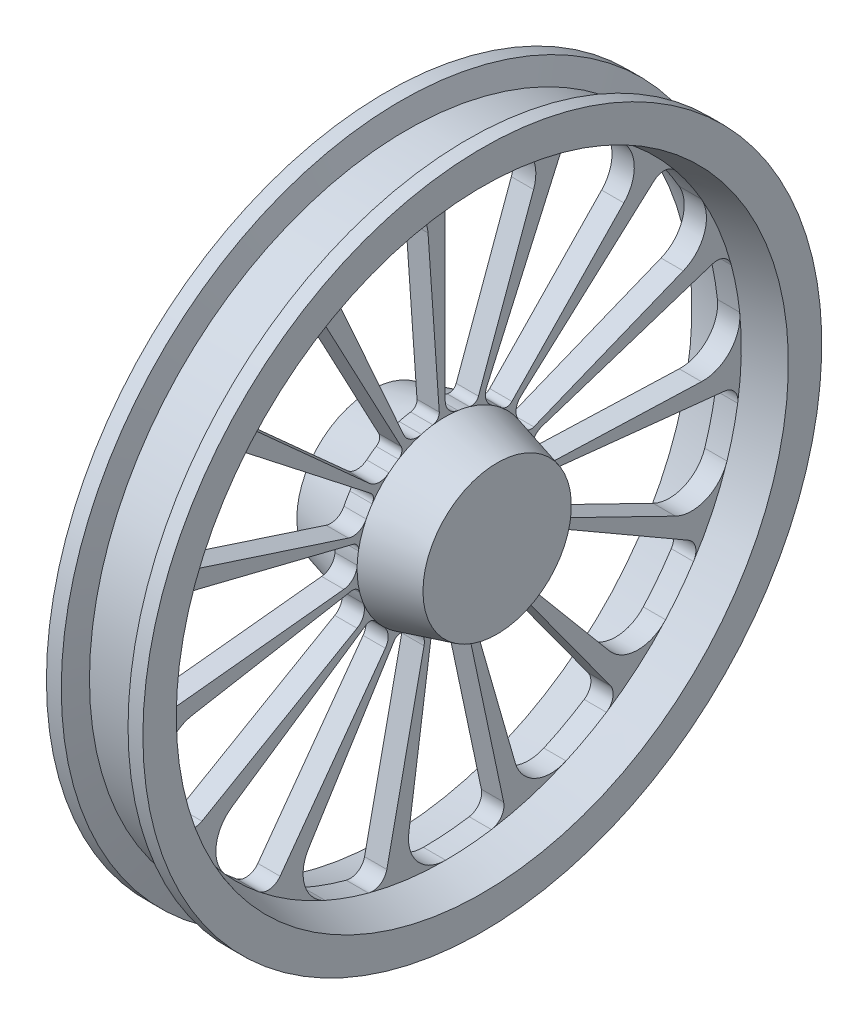
SolidWorks part; units mm, degrees
material "1060 Alloy"
ref_plane "Front Plane" through (0, 0, 0) normal (0, 0, 1) x (1, 0, 0)
ref_plane "Top Plane" through (0, 0, 0) normal (0, 1, 0) x (1, 0, 0)
ref_plane "Right Plane" through (0, 0, 0) normal (1, 0, 0) x (0, 0, -1)
sketch "Sketch1" plane through (0, 0, 0) normal (0, 1, 0) x (1, 0, 0)
  line L0 (0, 427.5) -> (0, -257.8979) construction
  line L1 (-372, 0) -> (372, 0) construction
  line L2 (-85, 0) -> (85, 0) construction
  line L3 (85, 0) -> (85, 100)
  line L4 (85, 100) -> (15, 118.7564)
  line L5 (15, 118.7564) -> (15, 399.1025)
  line L6 (15, 399.1025) -> (65, 412.5)
  line L7 (65, 412.5) -> (65, 457.5)
  line L8 (65, 457.5) -> (45, 457.5)
  line L9 (45, 457.5) -> (36.9615, 427.5)
  line L10 (36.9615, 427.5) -> (-36.9615, 427.5)
  line L11 (15, 118.7564) -> (91.7849, 118.7564) construction
  line L12 (-85, 0) -> (-85, 100)
  line L13 (36.9615, 427.5) -> (36.9615, 457.5) construction
  line L14 (15, 399.1025) -> (32.4139, 399.1025) construction
  line L15 (-85, 100) -> (-15, 118.7564)
  line L16 (-15, 118.7564) -> (-15, 399.1025)
  line L17 (-15, 399.1025) -> (-65, 412.5)
  line L18 (-65, 412.5) -> (-65, 457.5)
  line L19 (-65, 457.5) -> (-45, 457.5)
  line L20 (-45, 457.5) -> (-36.9615, 427.5)
  line L21 (-85, 0) -> (85, 0)
  point P4 (0, 0)
  point P8 (0, 0)
  point P21 (0, 0)
  dimension "D2" = 15
  dimension "D3" = 100
  dimension "D4" = 45
  dimension "D5" = 20
  dimension "D6" = 30
  dimension "D7" = 15
  dimension "D8" = 15
  dimension "D9" = 65
  dimension "D10" = 85
  dimension "D11" = 457.5
  dimension "D12" = 30
revolve "Revolve1" add sketch "Sketch1" angle 360 about L21
sketch "Sketch2" plane through (15, 0, 0) normal (1, 0, 0) x (0, 0, -1)
  line L0 (0, 457.5) -> (0, -457.5) construction
  line L1 (-457.5, 0) -> (457.5, 0) construction
  line L2 (0, 378.5746) -> (0, 137.3075)
  line L3 (119.0959, 324.4726) -> (44.8089, 120.3708)
  line L4 (153.9802, 345.8451) -> (55.848, 125.4366)
  line L5 (240.7744, 247.9799) -> (89.8942, 91.7388)
  line L6 (281.3358, 253.3159) -> (102.0394, 91.8767)
  line L7 (320.8208, 128.6091) -> (119.4359, 47.2443)
  line L8 (360.0459, 116.986) -> (130.5872, 42.4304)
  line L9 (345.3945, -12.9993) -> (128.3262, -5.4191)
  line L10 (376.5007, -39.5718) -> (136.5553, -14.3525)
  line L11 (310.2462, -152.3601) -> (115.0276, -57.1456)
  line L12 (327.8552, -189.2873) -> (118.9118, -68.6538)
  line L13 (221.4536, -265.3764) -> (81.8398, -98.991)
  line L14 (222.5206, -306.2733) -> (80.7073, -111.0841)
  line L15 (94.3697, -332.5067) -> (34.5011, -123.72)
  line L16 (78.7101, -370.3018) -> (28.5478, -134.307)
  line L17 (-49.0317, -342.1436) -> (-18.8032, -127.0567)
  line L18 (-78.7101, -370.3018) -> (-28.5478, -134.307)
  line L19 (-183.955, -292.6207) -> (-68.8562, -108.4241)
  line L20 (-222.5206, -306.2733) -> (-80.7073, -111.0841)
  line L21 (-287.0708, -192.5011) -> (-107.0033, -71.044)
  line L22 (-327.8552, -189.2873) -> (-118.9118, -68.6538)
  line L23 (-340.5495, -59.0963) -> (-126.6486, -21.3798)
  line L24 (-376.5007, -39.5718) -> (-136.5553, -14.3525)
  line L25 (-335.144, 84.5268) -> (-124.3952, 31.9812)
  line L26 (-360.0459, 116.986) -> (-130.5872, 42.4304)
  line L27 (-271.7892, 213.5344) -> (-100.6327, 79.8124)
  line L28 (-281.3358, 253.3159) -> (-102.0394, 91.8767)
  line L29 (-161.4395, 305.62) -> (-59.47, 113.8433)
  line L30 (-153.9802, 345.8451) -> (-55.848, 125.4366)
  line L31 (-23.1754, 344.8612) -> (-8.0243, 128.1896)
  circle A0 centre (0, 0) radius 457.5 construction
  arc A1 (0, 378.5746) -> (21.0551, 398.5468) centre (20, 378.5746) cw
  circle A2 centre (0, 0) radius 399.1025 construction
  arc A3 (0, 137.3075) -> (17.1173, 117.5164) centre (20, 137.3075) ccw
  circle A4 centre (0, 0) radius 118.7564 construction
  arc A5 (119.0959, 324.4726) -> (82.4393, 390.4953) centre (72.1112, 341.5736) ccw
  arc A6 (44.8089, 120.3708) -> (32.6616, 114.1767) centre (35.4119, 123.791) cw
  arc A8 (32.6616, 114.1767) -> (17.1173, 117.5164) centre (0, 0) ccw
  arc A10 (82.4393, 390.4953) -> (21.0551, 398.5468) centre (0, 0) ccw
  arc A11 (55.848, 125.4366) -> (63.4356, 100.3943) centre (74.1189, 117.3019) ccw
  arc A12 (76.2777, 91.0209) -> (63.4356, 100.3943) centre (0, 0) ccw
  arc A13 (89.8942, 91.7388) -> (76.2777, 91.0209) centre (82.7008, 98.6854) cw
  arc A14 (153.9802, 345.8451) -> (181.3384, 355.5267) centre (172.2511, 337.7104) cw
  arc A15 (234.1408, 323.2041) -> (181.3384, 355.5267) centre (0, 0) ccw
  arc A16 (240.7744, 247.9799) -> (234.1408, 323.2041) centre (204.8074, 282.7128) ccw
  arc A17 (102.0394, 91.8767) -> (98.7853, 65.9132) centre (115.422, 77.0138) ccw
  arc A18 (106.7047, 52.1268) -> (98.7853, 65.9132) centre (0, 0) ccw
  arc A19 (119.4359, 47.2443) -> (106.7047, 52.1268) centre (115.6899, 56.5162) cw
  arc A20 (281.3358, 253.3159) -> (310.2666, 251.0328) centre (294.7184, 238.453) cw
  arc A21 (345.3572, 200.028) -> (310.2666, 251.0328) centre (0, 0) ccw
  arc A22 (320.8208, 128.6091) -> (345.3572, 200.028) centre (302.0905, 174.9683) ccw
  arc A23 (130.5872, 42.4304) -> (117.0542, 20.0351) centre (136.7675, 23.4092) ccw
  arc A24 (118.6815, 4.2195) -> (117.0542, 20.0351) centre (0, 0) ccw
  arc A25 (128.3262, -5.4191) -> (118.6815, 4.2195) centre (128.6751, 4.5748) cw
  arc A26 (360.0459, 116.986) -> (385.5469, 103.1331) centre (366.2262, 97.9649) cw
  arc A27 (396.8583, 42.2653) -> (385.5469, 103.1331) centre (0, 0) ccw
  arc A28 (345.3945, -12.9993) -> (396.8583, 42.2653) centre (347.1394, 36.9702) ccw
  arc A29 (136.5553, -14.3525) -> (115.0833, -29.3073) centre (134.4647, -34.243) ccw
  arc A30 (110.1371, -44.4174) -> (115.0833, -29.3073) centre (0, 0) ccw
  arc A31 (115.0276, -57.1456) -> (110.1371, -44.4174) centre (119.4113, -48.1576) cw
  arc A32 (376.5007, -39.5718) -> (394.1626, -62.5993) centre (374.4102, -59.4623) cw
  arc A33 (379.7389, -122.8056) -> (394.1626, -62.5993) centre (0, 0) ccw
  arc A34 (310.2462, -152.3601) -> (379.7389, -122.8056) centre (332.1648, -107.4204) ccw
  arc A35 (118.9118, -68.6538) -> (93.2135, -73.5821) centre (108.9118, -85.9743) ccw
  arc A36 (82.5491, -85.3741) -> (93.2135, -73.5821) centre (0, 0) ccw
  arc A37 (81.8398, -98.991) -> (82.5491, -85.3741) centre (89.5002, -92.5631) cw
  arc A38 (327.8552, -189.2873) -> (334.6241, -217.5077) centre (317.8552, -206.6078) cw
  arc A39 (296.9592, -266.6422) -> (334.6241, -217.5077) centre (0, 0) ccw
  arc A40 (221.4536, -265.3764) -> (296.9592, -266.6422) centre (259.7558, -233.237) ccw
  arc A41 (80.7073, -111.0841) -> (55.2262, -105.134) centre (64.527, -122.8398) ccw
  arc A42 (40.6875, -111.5689) -> (55.2262, -105.134) centre (0, 0) ccw
  arc A43 (34.5011, -123.72) -> (40.6875, -111.5689) centre (44.1137, -120.9637) cw
  arc A44 (222.5206, -306.2733) -> (217.226, -334.807) centre (206.3402, -318.029) cw
  arc A45 (162.8326, -364.374) -> (217.226, -334.807) centre (0, 0) ccw
  arc A46 (94.3697, -332.5067) -> (162.8326, -364.374) centre (142.4327, -318.7248) ccw
  arc A47 (28.5478, -134.307) -> (7.6898, -118.5072) centre (8.9849, -138.4652) ccw
  arc A48 (-8.2092, -118.4724) -> (7.6898, -118.5072) centre (0, 0) ccw
  arc A49 (-18.8032, -127.0567) -> (-8.2092, -118.4724) centre (-8.9005, -128.4484) cw
  arc A50 (78.7101, -370.3018) -> (62.2675, -394.2152) centre (59.1471, -374.4601) cw
  arc A51 (0.5507, -399.1022) -> (62.2675, -394.2152) centre (0, 0) ccw
  arc A52 (-49.0317, -342.1436) -> (0.5507, -399.1022) centre (0.4817, -349.1022) ccw
  arc A53 (-28.5478, -134.307) -> (-41.1762, -111.3895) centre (-48.1108, -130.1488) ccw
  arc A54 (-55.6866, -104.8909) -> (-41.1762, -111.3895) centre (0, 0) ccw
  arc A55 (-68.8562, -108.4241) -> (-55.6866, -104.8909) centre (-60.3757, -113.7233) cw
  arc A56 (-78.7101, -370.3018) -> (-103.4575, -385.46) centre (-98.273, -366.1436) cw
  arc A57 (-161.8264, -364.822) -> (-103.4575, -385.46) centre (0, 0) ccw
  arc A58 (-183.955, -292.6207) -> (-161.8264, -364.822) centre (-141.5526, -319.1167) ccw
  arc A59 (-80.7073, -111.0841) -> (-82.9225, -85.0115) centre (-96.8877, -99.3284) ccw
  arc A60 (-93.5352, -73.1728) -> (-82.9225, -85.0115) centre (0, 0) ccw
  arc A61 (-107.0033, -71.044) -> (-93.5352, -73.1728) centre (-101.4114, -79.3344) cw
  arc A62 (-222.5206, -306.2733) -> (-251.2939, -310.0552) centre (-238.7009, -294.5176) cw
  arc A63 (-296.2222, -267.4607) -> (-251.2939, -310.0552) centre (0, 0) ccw
  arc A64 (-287.0708, -192.5011) -> (-296.2222, -267.4607) centre (-259.1112, -233.953) ccw
  arc A65 (-118.9118, -68.6538) -> (-110.3308, -43.9342) centre (-128.9118, -51.3332) ccw
  arc A66 (-115.2107, -28.8025) -> (-110.3308, -43.9342) centre (0, 0) ccw
  arc A67 (-126.6486, -21.3798) -> (-115.2107, -28.8025) centre (-124.9121, -31.2279) cw
  arc A68 (-327.8552, -189.2873) -> (-355.6792, -181.0391) centre (-337.8552, -171.9668) cw
  arc A69 (-379.3985, -123.8531) -> (-355.6792, -181.0391) centre (0, 0) ccw
  arc A70 (-340.5495, -59.0963) -> (-379.3985, -123.8531) centre (-331.8671, -108.3367) ccw
  arc A71 (-136.5553, -14.3525) -> (-118.6618, 4.7397) centre (-138.6459, 5.5379) ccw
  arc A72 (-116.9653, 20.548) -> (-118.6618, 4.7397) centre (0, 0) ccw
  arc A73 (-124.3952, 31.9812) -> (-116.9653, 20.548) centre (-126.8144, 22.2783) cw
  arc A74 (-376.5007, -39.5718) -> (-398.5643, -20.7197) centre (-378.5913, -19.6814) cw
  arc A75 (-396.9734, 41.1698) -> (-398.5643, -20.7197) centre (0, 0) ccw
  arc A76 (-335.144, 84.5268) -> (-396.9734, 41.1698) centre (-347.2401, 36.012) ccw
  arc A77 (-130.5872, 42.4304) -> (-106.4752, 52.594) centre (-124.4069, 61.4515) ccw
  arc A78 (-98.4955, 66.3456) -> (-106.4752, 52.594) centre (0, 0) ccw
  arc A79 (-100.6327, 79.8124) -> (-98.4955, 66.3456) centre (-106.7894, 71.9323) cw
  arc A80 (-360.0459, 116.986) -> (-372.5341, 143.1823) centre (-353.8655, 136.0071) cw
  arc A81 (-345.908, 199.0741) -> (-372.5341, 143.1823) centre (0, 0) ccw
  arc A82 (-271.7892, 213.5344) -> (-345.908, 199.0741) centre (-302.5722, 174.1339) ccw
  arc A83 (-102.0394, 91.8767) -> (-75.878, 91.3544) centre (-88.6567, 106.7395) ccw
  arc A84 (-62.9949, 100.6714) -> (-75.878, 91.3544) centre (0, 0) ccw
  arc A85 (-59.47, 113.8433) -> (-62.9949, 100.6714) centre (-68.2994, 109.1486) cw
  arc A86 (-281.3358, 253.3159) -> (-282.0893, 282.3268) centre (-267.9532, 268.1788) cw
  arc A87 (-235.0319, 322.5567) -> (-282.0893, 282.3268) centre (0, 0) ccw
  arc A88 (-161.4395, 305.62) -> (-235.0319, 322.5567) centre (-205.5869, 282.1465) ccw
  arc A89 (-55.848, 125.4366) -> (-32.1608, 114.3187) centre (-37.5771, 133.5714) ccw
  arc A90 (-16.6019, 117.5903) -> (-32.1608, 114.3187) centre (0, 0) ccw
  arc A91 (-8.0243, 128.1896) -> (-16.6019, 117.5903) centre (-17.9999, 127.4921) cw
  arc A92 (-153.9802, 345.8451) -> (-142.8688, 372.6545) centre (-135.7093, 353.9798) cw
  arc A93 (-83.5167, 390.2663) -> (-142.8688, 372.6545) centre (0, 0) ccw
  arc A94 (-23.1754, 344.8612) -> (-83.5167, 390.2663) centre (-73.0536, 341.3733) ccw
  point P7 (0, 0)
  point P11 (0, 0)
  point P198 (0, 0)
  dimension "D1" = 20
  dimension "D2" = 20
  dimension "D4" = 50
  dimension "D5" = 10
  dimension "D3" = 20
  dimension "D7" = 217.2006
  dimension "D6" = 15
extrude "Cut-Extrude1" cut sketch "Sketch2" against normal through all
equation "\"A\"= 130mm"
equation "\"B\"= 915mm"
